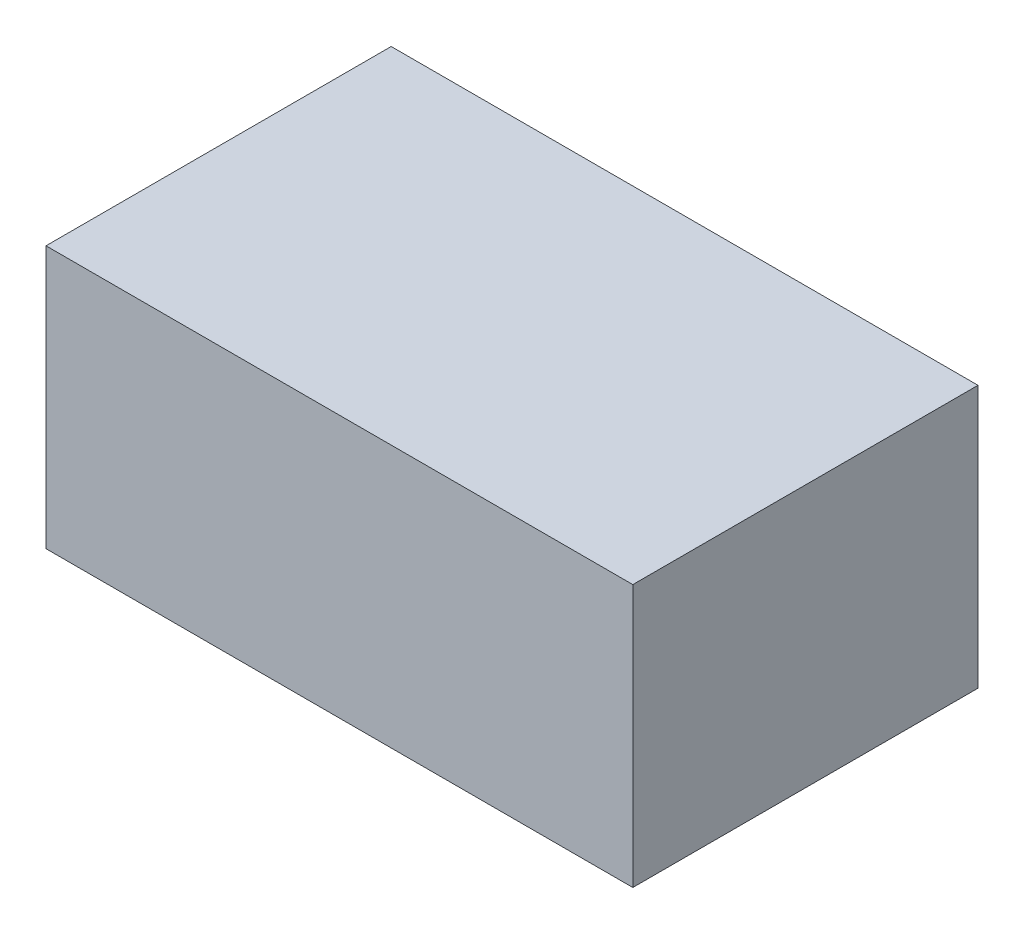
SolidWorks part; units mm, degrees
ref_plane "Front Plane" through (0, 0, 0) normal (0, 0, 1) x (1, 0, 0)
ref_plane "Top Plane" through (0, 0, 0) normal (0, 1, 0) x (1, 0, 0)
ref_plane "Right Plane" through (0, 0, 0) normal (1, 0, 0) x (0, 0, -1)
sketch "Esquisse1" plane through (0, 0, 0) normal (0, 1, 0) x (1, 0, 0)
  line L1 (0, 0) -> (53.975, 0)
  line L2 (0, 0) -> (0, 31.75)
  line L3 (0, 31.75) -> (53.975, 31.75)
  line L4 (53.975, 0) -> (53.975, 31.75)
  dimension "D1" = 53.975
  dimension "D2" = 31.75
extrude "Boss.-Extru.1" add sketch "Esquisse1" along normal mid plane 24.13
